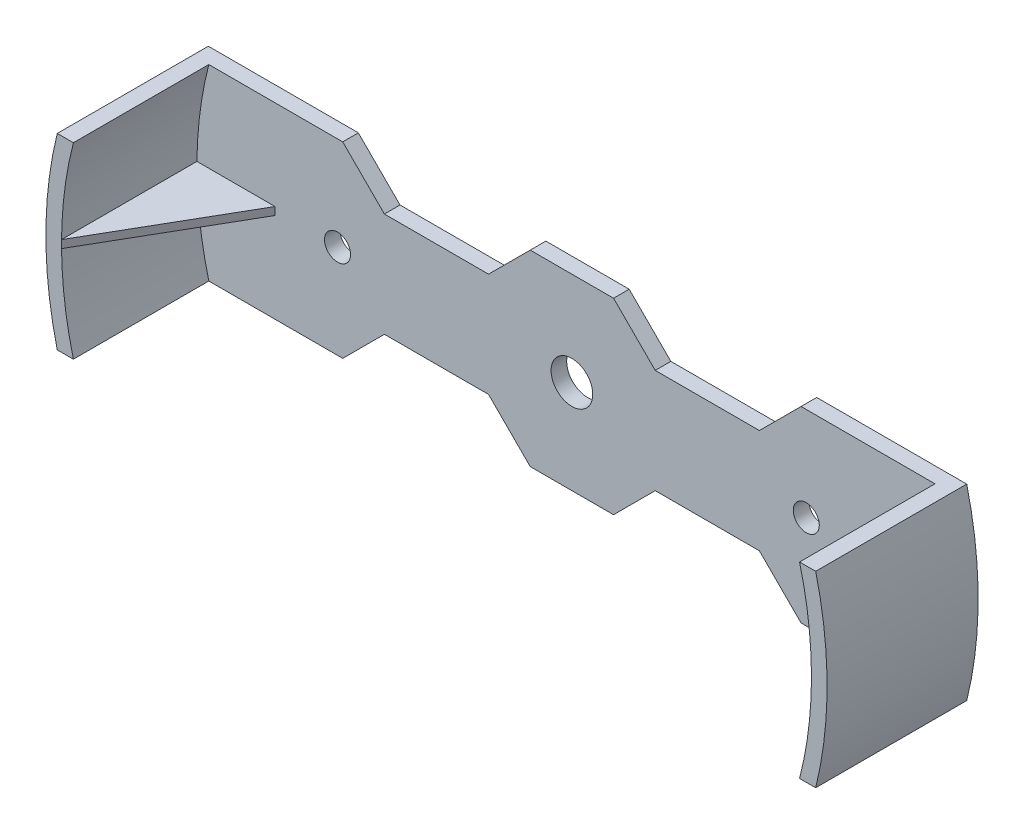
SolidWorks part; units mm, degrees
ref_plane "Front Plane" through (0, 0, 0) normal (0, 0, 1) x (1, 0, 0)
ref_plane "Top Plane" through (0, 0, 0) normal (0, 1, 0) x (1, 0, 0)
ref_plane "Right Plane" through (0, 0, 0) normal (1, 0, 0) x (0, 0, -1)
sketch "Sketch1" plane through (0, 0, 0) normal (0, 0, 1) x (1, 0, 0)
  line L0 (-72.808, 18) -> (8, 18)
  line L1 (-72.808, -18) -> (72.808, -18)
  line L2 (45, 0) -> (0, 0) construction
  line L3 (8, 18) -> (16, 10)
  line L4 (16, 10) -> (36, 10)
  line L5 (36, 10) -> (44, 18)
  line L9 (26, 10) -> (26, 0) construction
  line L10 (44, 18) -> (72.808, 18)
  line L11 (0, 0) -> (0, 9.0332) construction
  line L12 (36, -10) -> (44, -18)
  line L13 (8, -18) -> (16, -10)
  line L14 (16, -10) -> (36, -10)
  line L15 (-36, 10) -> (-44, 18)
  line L16 (-16, 10) -> (-36, 10)
  line L17 (-8, 18) -> (-16, 10)
  line L18 (-8, -18) -> (-16, -10)
  line L19 (-16, -10) -> (-36, -10)
  line L20 (-36, -10) -> (-44, -18)
  circle A0 centre (0, 0) radius 78
  circle A1 centre (0, 0) radius 4
  circle A2 centre (45, 0) radius 2.5
  circle A3 centre (-45, 0) radius 2.5
  circle A4 centre (0, 0) radius 75
  dimension "D1" = 156
  dimension "D2" = 3
  dimension "D5" = 5
  dimension "D6" = 8
  dimension "D7" = 5
  dimension "D3" = 18
  dimension "D4" = 18
  dimension "D8" = 45
  dimension "D9" = 45
  dimension "D10" = 10
  dimension "D11" = 45
  dimension "D12" = 36
  dimension "D13" = 26
extrude "Boss-Extrude1" add sketch "Sketch1" along normal blind 3 contours L0 A4 L1 A1 A2 A3
sketch "Sketch2" plane through (0, 0, 3) normal (0, 0, 1) x (1, 0, 0)
  line L0 (-72.808, 18) -> (-44, 18) construction
  line L1 (-72.808, -18) -> (-44, -18) construction
  line L6 (69.7137, -18) -> (-40.5, -18)
  line L7 (-69.7137, 18) -> (-72.808, 18)
  line L8 (-44, 18) -> (-72.808, 18)
  line L9 (-72.808, -18) -> (-44, -18)
  line L10 (-44, 18) -> (69.7137, 18)
  line L11 (-72.808, -18) -> (-69.7137, -18)
  line L30 (-44, -18) -> (-36, -10)
  line L31 (-44, -18) -> (-36, -10)
  line L32 (-36, -10) -> (-16, -10)
  line L33 (-36, -10) -> (-16, -10)
  line L34 (-16, -10) -> (-8, -18)
  line L35 (-16, -10) -> (-8, -18)
  line L36 (-8, -18) -> (8, -18)
  line L37 (-8, -18) -> (8, -18)
  line L38 (8, -18) -> (16, -10)
  line L39 (8, -18) -> (16, -10)
  line L40 (16, -10) -> (36, -10)
  line L41 (16, -10) -> (36, -10)
  line L42 (36, -10) -> (44, -18)
  line L43 (36, -10) -> (44, -18)
  line L44 (44, -18) -> (72.808, -18)
  line L45 (44, -18) -> (72.808, -18)
  line L46 (72.808, 18) -> (44, 18)
  line L47 (72.808, 18) -> (44, 18)
  line L48 (44, 18) -> (36, 10)
  line L49 (44, 18) -> (36, 10)
  line L50 (36, 10) -> (16, 10)
  line L51 (36, 10) -> (16, 10)
  line L52 (16, 10) -> (8, 18)
  line L53 (16, 10) -> (8, 18)
  line L54 (8, 18) -> (-8, 18)
  line L55 (8, 18) -> (-8, 18)
  line L56 (-8, 18) -> (-16, 10)
  line L57 (-8, 18) -> (-16, 10)
  line L58 (-16, 10) -> (-36, 10)
  line L59 (-16, 10) -> (-36, 10)
  line L60 (-36, 10) -> (-44, 18)
  line L61 (-36, 10) -> (-44, 18)
  arc A0 (69.7137, -18) -> (69.7137, 18) centre (0, 0) ccw
  arc A1 (69.8956, -17.28) -> (69.8956, 17.28) centre (0, 0) ccw construction
  arc A2 (-69.7137, 18) -> (-69.7137, -18) centre (0, 0) ccw
  arc A7 (-72.808, 18) -> (-72.808, -18) centre (0, 0) ccw
  arc A8 (72.808, -18) -> (72.808, 18) centre (0, 0) ccw
  arc A9 (-72.808, 18) -> (-72.808, -18) centre (0, 0) ccw
  arc A10 (72.808, -18) -> (72.808, 18) centre (0, 0) ccw
  arc A11 (-69.8956, 17.28) -> (-69.8956, -17.28) centre (0, 0) ccw construction
  point P12 (-69.8956, -18)
  point P15 (-69.7137, 18)
  point P18 (69.8956, 18)
  point P21 (69.7137, -18)
  arc M8 (72.808, -18) -> (72.808, 18) centre (0, 0) ccw
  line M30 (44, -18) -> (72.808, -18)
  line M31 (72.808, 18) -> (44, 18)
  dimension "D1" = 0
  dimension "D2" = 3
extrude "Boss-Extrude2" add sketch "Sketch2" along normal blind 26 contours A0 M30 M8 M31 | A9 L11 A2 L7
ref_plane "Plane1" through (0, 0, 0) normal (0, -1, 0) x (-1, 0, 0)
sketch "Sketch3" plane through (0, 0, 0) normal (0, -1, 0) x (-1, 0, 0)
  line L7 (-57, -3) -> (-72, -29)
  line L8 (69.7137, -3) -> (44, -3) construction
  line L9 (-69.7137, -29) -> (-72.808, -29) construction
  line L10 (-72, -29) -> (69.7137, -29) construction
  line L11 (-72, -29) -> (-72, -3)
  line L12 (-72, -3) -> (-69.7137, -3) construction
  line L13 (-72, -3) -> (-57, -3)
  line L14 (0, 0) -> (0, -21.5472)
  line L15 (72.808, 0) -> (-72.808, 0) construction
  line L16 (72, -29) -> (72, -3)
  line L17 (57, -3) -> (72, -29)
  line L18 (72, -3) -> (57, -3)
  dimension "D1" = 15
extrude "Boss-Extrude3" add sketch "Sketch3" along normal mid plane 1.5 contours L13 L11 L7 | L16 L18 L17
mirror "Mirror1" about plane through (0, 0, 0) normal (1, 0, 0) of "Boss-Extrude3"
